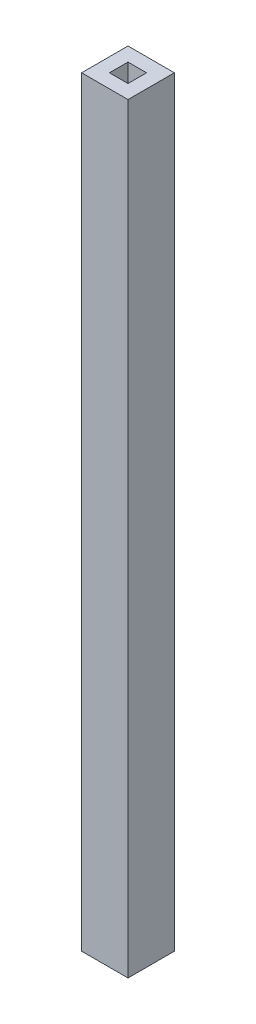
SolidWorks part; units mm, degrees
material "7075-T6 (SN)"
ref_plane "Front Plane" through (0, 0, 0) normal (0, 0, 1) x (1, 0, 0)
ref_plane "Top Plane" through (0, 0, 0) normal (0, 1, 0) x (1, 0, 0)
ref_plane "Right Plane" through (0, 0, 0) normal (1, 0, 0) x (0, 0, -1)
sketch "Sketch1" plane through (0, 0, 0) normal (0, 1, 0) x (1, 0, 0)
  line L1 (-2.5, 2.5) -> (2.5, 2.5)
  line L2 (-2.5, 2.5) -> (-2.5, -2.5)
  line L3 (-2.5, -2.5) -> (2.5, -2.5)
  line L4 (2.5, 2.5) -> (2.5, -2.5)
  line L5 (-2.5, 2.5) -> (2.5, -2.5) construction
  line L6 (-2.5, -2.5) -> (2.5, 2.5) construction
  line L7 (-1, 1) -> (1, 1)
  line L8 (-1, 1) -> (-1, -1)
  line L9 (-1, -1) -> (1, -1)
  line L10 (1, 1) -> (1, -1)
  line L11 (-1, 1) -> (1, -1) construction
  line L12 (-1, -1) -> (1, 1) construction
  point P0 (0, 0)
  point P6 (0, 0)
  dimension "D1" = 5
  dimension "D2" = 1.5
extrude "Boss-Extrude1" add sketch "Sketch1" along normal blind 82 contours L4 L1 L2 L3 L7 L10 L9 L8
